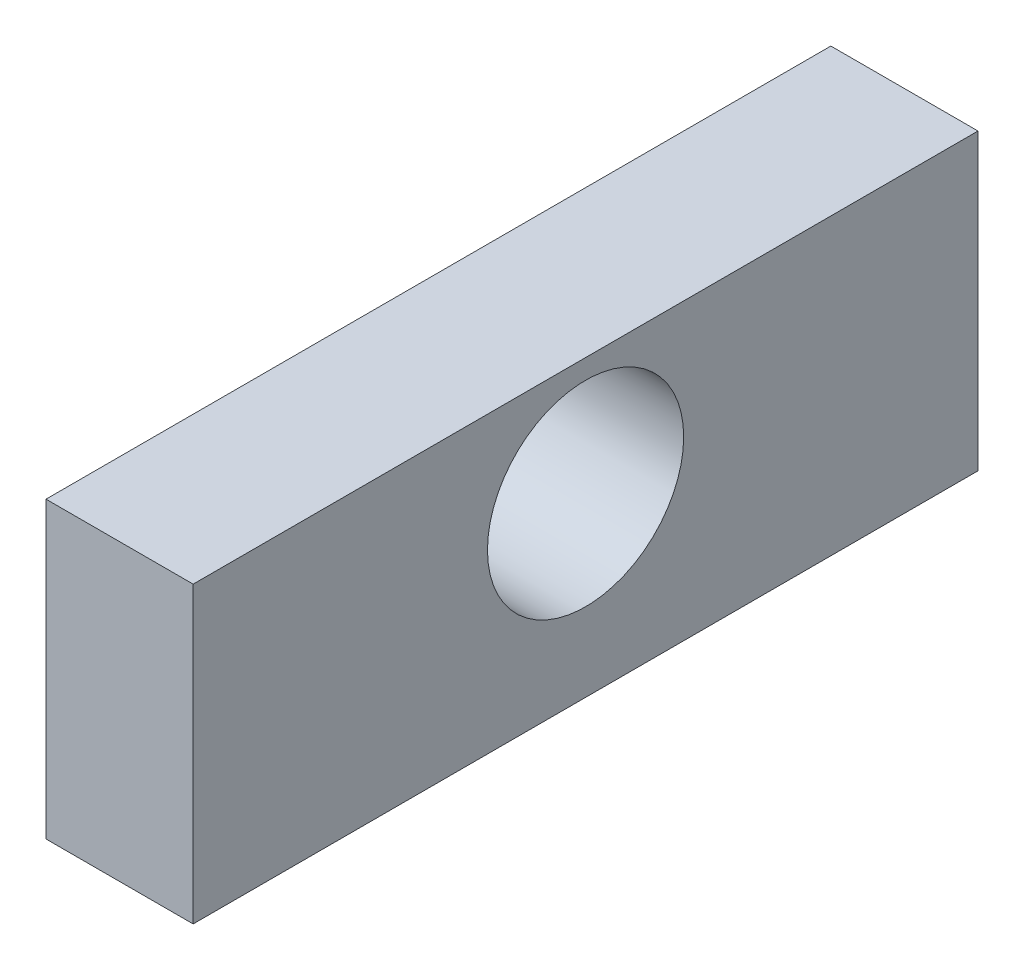
SolidWorks part; units mm, degrees
material "1060 Alloy"
ref_plane "Front Plane" through (0, 0, 0) normal (0, 0, 1) x (1, 0, 0)
ref_plane "Top Plane" through (0, 0, 0) normal (0, 1, 0) x (1, 0, 0)
ref_plane "Right Plane" through (0, 0, 0) normal (1, 0, 0) x (0, 0, -1)
sketch "Sketch1" plane through (0, 0, 0) normal (1, 0, 0) x (0, 0, -1)
  line L1 (-25.4, -9.525) -> (25.4, -9.525)
  line L2 (-25.4, -9.525) -> (-25.4, 9.525)
  line L3 (-25.4, 9.525) -> (25.4, 9.525)
  line L4 (25.4, -9.525) -> (25.4, 9.525)
  line L5 (-25.4, -9.525) -> (25.4, 9.525) construction
  line L6 (-25.4, 9.525) -> (25.4, -9.525) construction
  point P0 (0, 0)
  dimension "D1" = 50.8
  dimension "D2" = 19.05
extrude "Boss-Extrude1" add sketch "Sketch1" along normal blind 9.525
hole_wizard "1/2 (0.5) Diameter Hole1" positions "Sketch9" profile "Sketch8" hole size "1/2" standard "ANSI Inch"
sketch "Sketch9" plane through (9.525, 0, 0) normal (1, 0, 0) x (0, 0, -1)
  line L0 (-25.4, -9.525) -> (25.4, -9.525) construction
  point P0 (0, 1.905)
  dimension "D1" = 11.43
sketch "Sketch8" plane through (9.525, 1.905, 0) normal (0, 1, 0) x (0, 0, -1)
  line L0 (0, 0) -> (0, 73.9195)
  line L1 (0, 73.9195) -> (6.35, 70.104)
  line L2 (6.35, 70.104) -> (6.35, 0)
  line L5 (6.35, 0) -> (0, 0)
  line L10 (0, 73.9195) -> (-6.35, 70.104) construction
  line L11 (0, -6.35) -> (0, 107.95) construction
  dimension "Hole Dia." = 12.7
  dimension "Hole Depth" = 70.104
  dimension "Drill Angle" = 118
hole_wizard "#10-32 Tapped Hole1" positions "Sketch11" profile "Sketch10" tap size "#10-32" standard "ANSI Inch"
sketch "Sketch11" plane through (-1.1365, 0.5118, -25.4) normal (0, 0, -1) x (-1, 0, 0)
  line L0 (-10.6615, 9.0132) -> (-1.1365, 9.0132) construction
  line L2 (-10.6615, -10.0368) -> (-1.1365, -10.0368) construction
  line L3 (-10.6615, 9.0132) -> (-1.1365, 9.0132) construction
  point P0 (-5.899, -3.6868)
  point P2 (-5.899, 5.2032)
  point P6 (-5.899, 9.0132)
  dimension "D1" = 0
  dimension "D2" = 0
  dimension "D3" = 3.81
  dimension "D4" = 6.35
sketch "Sketch10" plane through (4.7625, -3.175, -25.4) normal (1, 0, 0) x (0, 1, 0)
  line L0 (0, 0) -> (0, 13.1513)
  line L1 (0, 13.1513) -> (2.0193, 11.938)
  line L2 (2.0193, 11.938) -> (2.0193, 0)
  line L5 (2.0193, 0) -> (0, 0)
  line L10 (0, 13.1513) -> (-2.0193, 11.938) construction
  line L11 (0, -6.35) -> (0, 107.95) construction
  dimension "Tap Drill Dia." = 4.0386
  dimension "Tap Drill Depth" = 11.938
  dimension "Drill Angle" = 118
cosmetic thread "Hole Thread1" parameters "D1"=9.652, "D2"=4.826
cosmetic thread "Hole Thread2" parameters "D1"=9.652, "D2"=4.826
